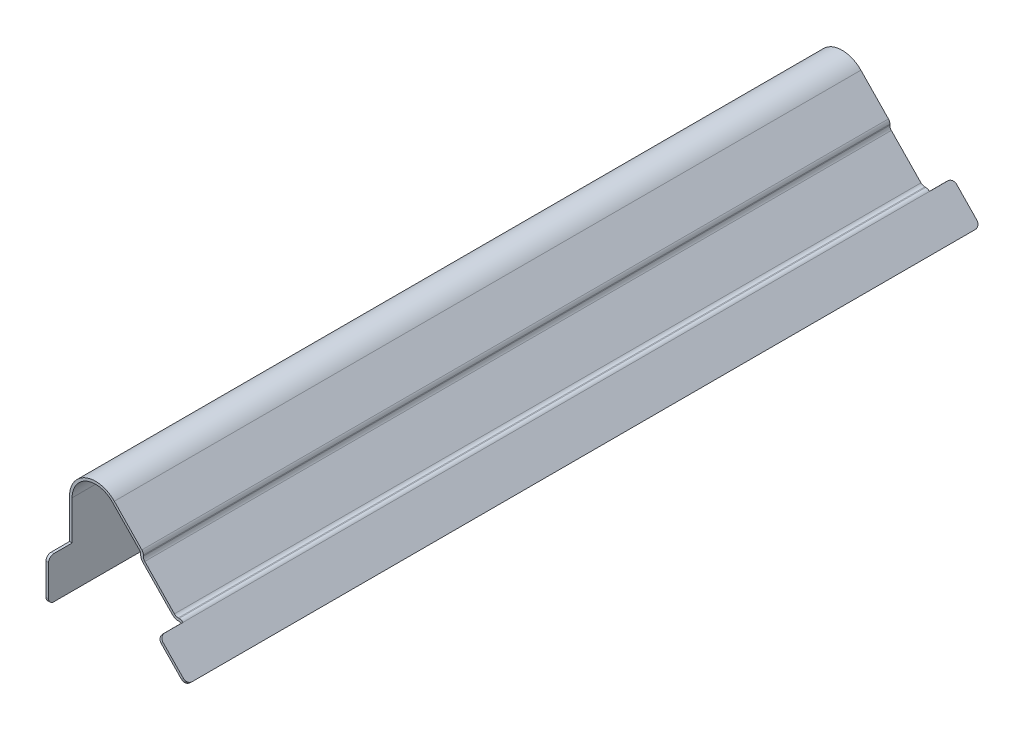
SolidWorks part; units mm, degrees
ref_plane "Front Plane" through (0, 0, 0) normal (0, 0, 1) x (1, 0, 0)
ref_plane "Top Plane" through (0, 0, 0) normal (0, 1, 0) x (1, 0, 0)
ref_plane "Right Plane" through (0, 0, 0) normal (1, 0, 0) x (0, 0, -1)
sketch "Sketch1" plane through (0, 0, 0) normal (0, 0, 1) x (1, 0, 0)
  line L0 (0, 0) -> (0, 15.5)
  line L1 (8.589, 18.9812) -> (13.8643, 13.5425)
  line L2 (14.1461, 12.8158) -> (14.1403, 12.6257)
  line L3 (14.422, 11.899) -> (20.0989, 6.0462)
  line L4 (20.8167, 5.7425) -> (21.0069, 5.7425)
  line L5 (21.7247, 5.4387) -> (27, 0)
  line L6 (0.5, 0) -> (0.5, 15.5)
  line L7 (8.2301, 18.6331) -> (13.5054, 13.1944)
  line L8 (13.6463, 12.831) -> (13.6405, 12.6409)
  line L9 (14.0631, 11.5508) -> (19.74, 5.6981)
  line L10 (20.8167, 5.2425) -> (21.0069, 5.2425)
  line L11 (21.3658, 5.0906) -> (26.6411, -0.3481)
  line L12 (0, 0) -> (0.5, 0)
  line L13 (27, 0) -> (26.6411, -0.3481)
  arc A0 (8.589, 18.9812) -> (0, 15.5) centre (5, 15.5) ccw
  arc A1 (21.7247, 5.4387) -> (21.0069, 5.7425) centre (21.0069, 4.7425) ccw
  arc A2 (20.0989, 6.0462) -> (20.8167, 5.7425) centre (20.8167, 6.7425) ccw
  arc A3 (14.1403, 12.6257) -> (14.422, 11.899) centre (15.1398, 12.5952) ccw
  arc A4 (13.8643, 13.5425) -> (14.1461, 12.8158) centre (13.1465, 12.8463) cw
  arc A5 (8.2301, 18.6331) -> (0.5, 15.5) centre (5, 15.5) ccw
  arc A6 (13.5054, 13.1944) -> (13.6463, 12.831) centre (13.1465, 12.8463) cw
  arc A7 (13.6405, 12.6409) -> (14.0631, 11.5508) centre (15.1398, 12.5952) ccw
  arc A8 (19.74, 5.6981) -> (20.8167, 5.2425) centre (20.8167, 6.7425) ccw
  arc A9 (21.3658, 5.0906) -> (21.0069, 5.2425) centre (21.0069, 4.7425) ccw
  point P11 (21.4301, 5.7425)
  point P15 (20.3935, 5.7425)
  point P19 (14.1274, 12.2027)
  point P22 (14.159, 13.2388)
  dimension "D3" = 5
  dimension "D4" = 9
  dimension "D5" = 8
  dimension "D7" = 1
  dimension "D1" = 20.5
  dimension "D2" = 27
  dimension "D6" = 8
  dimension "D8" = 0.5
extrude "Boss-Extrude1" add sketch "Sketch1" along normal mid plane 143 contours L0 A0 L1 A4 L2 A3 L3 A2 L4 A1 L5 L13 L11 A9 L10 A8 L9 A7 L8 A6 L7 A5 L6 L12
sketch "Sketch2" plane through (0, 0, 0) normal (1, 0, 0) x (0, 0, -1)
  line L0 (-71.5, 0) -> (-75, 0)
  line L1 (-76, 1) -> (-76, 7)
  line L2 (-75, 8) -> (-71.5, 8)
  line L3 (-71.5, 0) -> (-71.5, 15.5) construction
  line L4 (-71.5, 8) -> (-71.5, 0)
  line L5 (0, 0) -> (0, 20.5) construction
  line L6 (-71.5, 0) -> (71.5, 0) construction
  line L7 (71.5, 20.5) -> (-71.5, 20.5) construction
  line L8 (71.5, 8) -> (71.5, 0)
  line L9 (75, 8) -> (71.5, 8)
  line L10 (76, 1) -> (76, 7)
  line L11 (71.5, 0) -> (75, 0)
  arc A0 (76, 1) -> (75, 0) centre (75, 1) cw
  arc A1 (76, 7) -> (75, 8) centre (75, 7) ccw
  arc A2 (-75, 0) -> (-76, 1) centre (-75, 1) cw
  arc A3 (-76, 7) -> (-75, 8) centre (-75, 7) cw
  point P20 (76, 0)
  point P23 (76, 8)
  point P26 (-76, 0)
  point P29 (-76, 8)
  dimension "D3" = 1
  dimension "D1" = 8
  dimension "D2" = 152
extrude "Boss-Extrude2" add sketch "Sketch2" along normal blind 0.5
sketch "Sketch3" plane through (13.9117, 13.4937, 0) normal (0.7178, 0.6962, 0) x (0, 0, -1)
  line L0 (-71.5, -11.2217) -> (-75, -11.2217)
  line L1 (-76, -12.2217) -> (-76, -17.7985)
  line L2 (-75, -18.7985) -> (-71.5, -18.7985)
  line L3 (-71.5, -18.7985) -> (-71.5, -11.2217)
  line L4 (0, -18.7985) -> (0, -0.7822) construction
  line L5 (-71.5, -18.7985) -> (71.5, -18.7985) construction
  line L6 (-71.5, -0.7822) -> (71.5, -0.7822) construction
  line L7 (71.5, -18.7985) -> (71.5, -11.2217)
  line L8 (75, -18.7985) -> (71.5, -18.7985)
  line L9 (76, -12.2217) -> (76, -17.7985)
  line L10 (71.5, -11.2217) -> (75, -11.2217)
  arc A0 (75, -18.7985) -> (76, -17.7985) centre (75, -17.7985) ccw
  arc A1 (76, -12.2217) -> (75, -11.2217) centre (75, -12.2217) ccw
  arc A2 (-76, -17.7985) -> (-75, -18.7985) centre (-75, -17.7985) ccw
  arc A3 (-75, -11.2217) -> (-76, -12.2217) centre (-75, -12.2217) ccw
  point P18 (76, -18.7985)
  point P21 (76, -11.2217)
  point P24 (-76, -18.7985)
  point P27 (-76, -11.2217)
  dimension "D2" = 1
  dimension "D1" = 152
extrude "Boss-Extrude3" add sketch "Sketch3" against normal blind 0.5 contours L1 A2 L2 L3 L0 A3 | L9 A0 L8 L7 L10 A1
